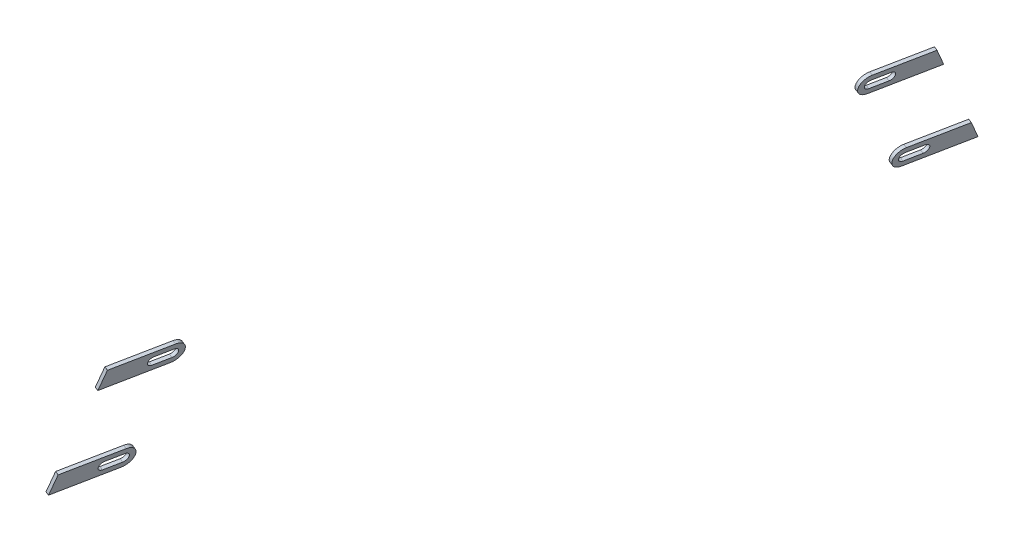
SolidWorks part; units mm, degrees
material "AISI 4130 Steel, normalized at 870C"
ref_plane "Front Plane" through (0, 0, 0) normal (0, 0, 1) x (1, 0, 0)
ref_plane "Top Plane" through (0, 0, 0) normal (0, 1, 0) x (1, 0, 0)
ref_plane "Right Plane" through (0, 0, 0) normal (1, 0, 0) x (0, 0, -1)
ref_plane "Plane1" through (-647.7275, 206.835, -128.8296) normal (0.936, -0.2989, 0.1862) x (0.1773, -0.0566, -0.9825)
ref_plane "Plane2" through (-659.6142, 210.6307, -131.1938) normal (-0.936, 0.2989, -0.1862) x (-0.1773, 0.0566, 0.9825)
sketch3d "3DSketch1"
  line L0 (-74.706, 1127.2095, -1532.204) -> (-334.6494, 378.679, -1427.0247) construction
  line L1 (-74.706, 1127.2095, -1532.204) -> (-240, 340, -1965) construction
  line L2 (-74.706, 1127.2095, -1532.204) -> (-334.6494, 378.679, -1427.0247) construction
  line L3 (-74.706, 1127.2095, -1532.204) -> (-240, 340, -1965) construction
  line L4 (-118.2147, 920, -1646.1247) -> (-146.6639, 920, -1503.0881) construction
  line L5 (-118.2147, 920, -1646.1247) -> (-146.6639, 920, -1503.0881) construction
sketch "Sketch2" plane through (-659.6142, 210.6307, -131.1938) normal (-0.936, 0.2989, -0.1862) x (-0.1773, 0.0566, 0.9825)
  line L0 (-1762.4286, 444.1799) -> (-1724.6424, 441.9337)
  line L2 (-1723.9303, 453.9125) -> (-1756.0208, 455.8201)
  line L6 (-1544.2893, 840.4421) -> (-1398.708, 831.7881) construction
  line L7 (-1756.0208, 455.8201) -> (-1762.4286, 444.1799)
  line L8 (-1428.3419, 1051.0671) -> (-1868.8378, 250.8817) construction
  line L11 (-1759.2247, 450) -> (-1718.297, 447.5671) construction
  line L12 (-1734.2688, 448.5165) -> (-1724.2864, 447.9231) construction
  line L13 (-1734.1056, 451.2617) -> (-1724.1232, 450.6683)
  line L14 (-1734.4319, 445.7713) -> (-1724.4496, 445.178)
  arc A0 (-1723.9303, 453.9125) -> (-1724.6424, 441.9337) centre (-1724.2864, 447.9231) cw
  arc A2 (-1734.1056, 451.2617) -> (-1734.4319, 445.7713) centre (-1734.2688, 448.5165) ccw
  arc A3 (-1724.4496, 445.178) -> (-1724.1232, 450.6683) centre (-1724.2864, 447.9231) ccw
  point P2 (0, 0)
  point P7 (-1759.2247, 450)
  point P14 (-1729.2776, 448.2198)
  point P21 (-1743.5355, 443.0568)
  dimension "D4" = 10
  dimension "D5" = 2.75
  dimension "D1" = 450
  dimension "D2" = 12
  dimension "D3" = 35
extrude "Boss-Extrude1" add sketch "Sketch2" along normal blind 2
sketch "Sketch4" plane through (-659.6142, 210.6307, -131.1938) normal (-0.936, 0.2989, -0.1862) x (-0.1773, 0.0566, 0.9825)
  line L0 (-1789.0503, 395.8201) -> (-1756.8982, 393.9089)
  line L1 (-1428.3419, 1051.0671) -> (-1868.8378, 250.8817) construction
  line L3 (-1757.6103, 381.93) -> (-1795.4582, 384.1799)
  line L4 (-1795.4582, 384.1799) -> (-1789.0503, 395.8201)
  line L5 (-1544.2893, 840.4421) -> (-1398.708, 831.7881) construction
  line L6 (-1792.2542, 390) -> (-1751.2648, 387.5634) construction
  line L7 (-1767.2366, 388.5128) -> (-1757.2542, 387.9194) construction
  line L8 (-1767.0734, 391.258) -> (-1757.0911, 390.6646)
  line L9 (-1767.3998, 385.7677) -> (-1757.4174, 385.1743)
  arc A0 (-1756.8982, 393.9089) -> (-1757.6103, 381.93) centre (-1757.2542, 387.9194) cw
  arc A1 (-1767.0734, 391.258) -> (-1767.3998, 385.7677) centre (-1767.2366, 388.5128) ccw
  arc A2 (-1757.4174, 385.1743) -> (-1757.0911, 390.6646) centre (-1757.2542, 387.9194) ccw
  point P10 (-1792.2542, 390)
  point P17 (-1762.2454, 388.2161)
  point P22 (0, 0)
  dimension "D3" = 35
  dimension "D5" = 2.75
  dimension "D1" = 12
  dimension "D2" = 390
  dimension "D4" = 10
extrude "Boss-Extrude2" add sketch "Sketch4" along normal blind 2 separate body
sketch "Sketch5" plane through (-659.6142, 210.6307, -131.1938) normal (-0.936, 0.2989, -0.1862) x (-0.1773, 0.0566, 0.9825)
  line L0 (-1428.3419, 1051.0671) -> (-1321.2913, 258.9362) construction
  line L1 (-1344.5935, 431.363) -> (-1342.9558, 419.2445)
  line L2 (-1342.9558, 419.2445) -> (-1379.069, 421.3912)
  line L4 (-1378.3569, 433.3701) -> (-1344.5935, 431.363)
  line L5 (-1544.2893, 840.4421) -> (-1398.708, 831.7881) construction
  line L6 (-1384.7024, 427.7367) -> (-1343.7746, 425.3037) construction
  line L7 (-1378.713, 427.3806) -> (-1368.7306, 426.7872) construction
  line L8 (-1378.5498, 430.1258) -> (-1368.5674, 429.5324)
  line L9 (-1378.8761, 424.6355) -> (-1368.8938, 424.0421)
  line L10 (-1718.297, 447.5671) -> (-1384.7024, 427.7367) construction
  arc A0 (-1378.3569, 433.3701) -> (-1379.069, 421.3912) centre (-1378.713, 427.3806) ccw
  arc A1 (-1378.5498, 430.1258) -> (-1378.8761, 424.6355) centre (-1378.713, 427.3806) ccw
  arc A2 (-1368.8938, 424.0421) -> (-1368.5674, 429.5324) centre (-1368.7306, 426.7872) ccw
  arc A3 (-1724.6424, 441.9337) -> (-1723.9303, 453.9125) centre (-1724.2864, 447.9231) ccw construction
  point P0 (-1343.7746, 425.3037)
  point P16 (-1373.7218, 427.0839)
  dimension "D3" = 35
  dimension "D5" = 2.75
  dimension "D1" = 425.3037
  dimension "D2" = 12
  dimension "D4" = 10
extrude "Boss-Extrude3" add sketch "Sketch5" along normal blind 2 separate body
sketch "Sketch6" plane through (-659.6142, 210.6307, -131.1938) normal (-0.936, 0.2989, -0.1862) x (-0.1773, 0.0566, 0.9825)
  line L0 (-1428.3419, 1051.0671) -> (-1321.2913, 258.9362) construction
  line L1 (-1336.1518, 368.8978) -> (-1334.5141, 356.7792)
  line L2 (-1334.5141, 356.7792) -> (-1370.6273, 358.926)
  line L4 (-1369.9152, 370.9048) -> (-1336.1518, 368.8978)
  line L5 (-1544.2893, 840.4421) -> (-1398.708, 831.7881) construction
  line L6 (-1751.2648, 387.5634) -> (-1376.2607, 365.2714) construction
  line L7 (-1370.2712, 364.9154) -> (-1360.2889, 364.322) construction
  line L8 (-1370.1081, 367.6605) -> (-1360.1257, 367.0671)
  line L9 (-1370.4344, 362.1702) -> (-1360.4521, 361.5768)
  arc A0 (-1369.9152, 370.9048) -> (-1370.6273, 358.926) centre (-1370.2712, 364.9154) ccw
  arc A1 (-1757.6103, 381.93) -> (-1756.8982, 393.9089) centre (-1757.2542, 387.9194) ccw construction
  arc A2 (-1370.1081, 367.6605) -> (-1370.4344, 362.1702) centre (-1370.2712, 364.9154) ccw
  arc A3 (-1360.4521, 361.5768) -> (-1360.1257, 367.0671) centre (-1360.2889, 364.322) ccw
  point P0 (-1335.3329, 362.8385)
  point P17 (-1365.2801, 364.6187)
  dimension "D4" = 2.75
  dimension "D1" = 12
  dimension "D2" = 35
  dimension "D3" = 10
extrude "Boss-Extrude4" add sketch "Sketch6" along normal blind 2 separate body
